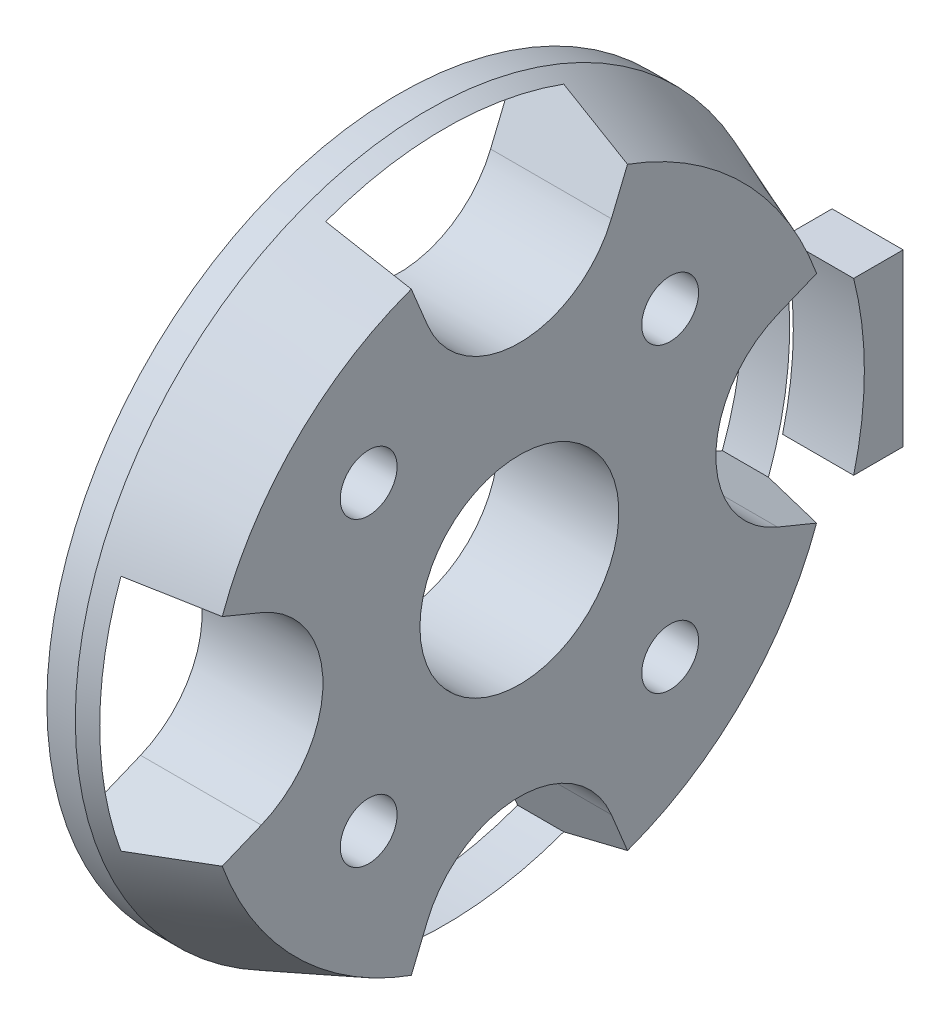
SolidWorks part; units mm, degrees
ref_plane "Front Plane" through (0, 0, 0) normal (0, 0, 1) x (1, 0, 0)
ref_plane "Top Plane" through (0, 0, 0) normal (0, 1, 0) x (1, 0, 0)
ref_plane "Right Plane" through (0, 0, 0) normal (1, 0, 0) x (0, 0, -1)
sketch "Sketch2" plane through (0, 0, 0) normal (0, 0, 1) x (1, 0, 0)
  line L0 (0, 0) -> (51.0154, 0) construction
  line L1 (0, 24.75) -> (2, 24.75)
  line L2 (2, 24.75) -> (8.5, 22.25)
  line L3 (8.5, 22.25) -> (8.5, 7)
  line L4 (8.5, 7) -> (0, 7)
  line L5 (0, 7) -> (0, 24.75)
  dimension "D1" = 8.5
  dimension "D2" = 2
  dimension "D3" = 2.5
  dimension "D4" = 14
  dimension "D5" = 49.5
revolve "Revolve1" add sketch "Sketch2" angle 360 about L0
sketch "Sketch3" plane through (8.5, 0, 0) normal (1, 0, 0) x (0, 0, -1)
  line L0 (0, 0) -> (10.6066, 10.6066) construction
  line L1 (0, 0) -> (5.0555, 0) construction
  circle A0 centre (10.6066, 10.6066) radius 2
  circle A1 centre (10.6066, -10.6066) radius 2
  circle A2 centre (-10.6066, -10.6066) radius 2
  circle A3 centre (-10.6066, 10.6066) radius 2
  point P14 (0, 0)
  dimension "D2" = 4
  dimension "D1" = 45
  dimension "D3" = 15
  dimension "D4" = 4
extrude "Cut-Extrude1" cut sketch "Sketch3" against normal blind 5
sketch "Sketch4" plane through (8.5, 0, 0) normal (1, 0, 0) x (0, 0, -1)
  line L0 (0, 0) -> (15, 0) construction
  line L1 (15, 6) -> (27, 6)
  line L2 (15, 6) -> (15, -6)
  line L3 (15, -6) -> (27, -6)
  line L4 (27, 6) -> (27, -6)
  dimension "D1" = 12
  dimension "D2" = 12
  dimension "D3" = 15
extrude "Boss-Extrude1" add sketch "Sketch4" against normal blind 5
sketch "Sketch6" plane through (8.5, 0, 0) normal (1, 0, 0) x (0, 0, -1)
  line L0 (8.8598, 93.3826) -> (181.5264, 93.3826) construction
  line L1 (-6.4723, 18.1576) -> (-7.606, 20.9096)
  line L2 (6.4723, 18.1576) -> (7.606, 20.9096)
  line L3 (0, 0) -> (0, 20.8239) construction
  line L4 (-7.606, 20.9096) -> (-8.3768, 22.7807)
  line L5 (7.606, 20.9096) -> (8.3768, 22.7807)
  arc A0 (-6.4723, 18.1576) -> (6.4723, 18.1576) centre (0, 20.8239) ccw
  arc A1 (-7.606, 20.9096) -> (7.606, 20.9096) centre (0, 0) cw construction
  arc A2 (21.4257, 6) -> (21.4257, -6) centre (0, 0) ccw construction
  arc A3 (8.3768, 22.7807) -> (-8.3768, 22.7807) centre (0, 0) ccw
  dimension "D1" = 7
  dimension "D2" = 5
extrude "Cut-Extrude2" cut sketch "Sketch6" against normal through all
pattern_circular "CirPattern1" count 4 over 360 about axis through (0, 0, 0) along (1, 0, 0) of "Cut-Extrude2"
